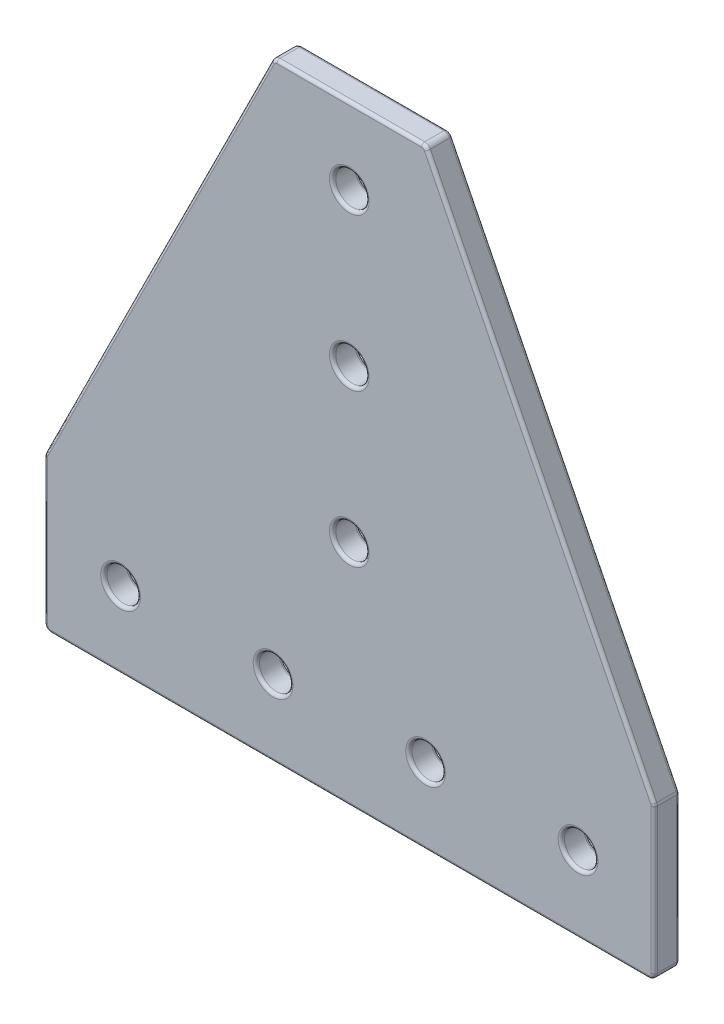
SolidWorks part; units mm, degrees
ref_plane "Front Plane" through (0, 0, 0) normal (0, 0, 1) x (1, 0, 0)
ref_plane "Top Plane" through (0, 0, 0) normal (0, 1, 0) x (1, 0, 0)
ref_plane "Right Plane" through (0, 0, 0) normal (1, 0, 0) x (0, 0, -1)
sketch "Sketch1" plane through (0, 0, 0) normal (0, 0, 1) x (1, 0, 0)
  line L1 (-76.2, -19.05) -> (76.2, -19.05) construction
  line L2 (76.2, -19.05) -> (76.2, 19.05) construction
  line L3 (76.2, 19.05) -> (19.05, 133.35) construction
  line L4 (19.05, 133.35) -> (-19.05, 133.35) construction
  line L6 (-19.05, 0) -> (-57.15, 0) construction
  line L7 (-72.0857, 8.1026) -> (-52.9331, 8.1026) construction
  line L8 (-72.0857, -8.1026) -> (-52.9331, -8.1026) construction
  line L9 (-76.2, -19.05) -> (-76.2, 19.05)
  line L10 (-76.2, 19.05) -> (-19.05, 133.35) construction
  line L11 (-19.05, 0) -> (19.05, 0) construction
  line L12 (19.05, 0) -> (57.15, 0) construction
  line L13 (0, 0) -> (0, 38.1) construction
  line L14 (0, 38.1) -> (0, 76.2) construction
  line L15 (0, 76.2) -> (0, 114.3) construction
  circle A0 centre (-57.15, 0) radius 4.1656 construction
  circle A1 centre (-19.05, 0) radius 4.1656 construction
  circle A4 centre (-57.15, 0) radius 3.9687 construction
  arc A6 (-72.0857, 8.1026) -> (-72.0857, -8.1026) centre (-62.3062, 0) ccw construction
  circle A7 centre (19.05, 0) radius 4.1656 construction
  arc A8 (-52.9331, -8.1026) -> (-52.9331, 8.1026) centre (-62.7126, 0) ccw construction
  circle A9 centre (57.15, 0) radius 4.1656 construction
  circle A10 centre (0, 38.1) radius 4.1656 construction
  circle A11 centre (0, 76.2) radius 4.1656 construction
  circle A12 centre (0, 114.3) radius 4.1656 construction
  point P4 (0, 0)
  point P9 (0, -19.05)
  point P14 (0, 133.35)
  point P20 (-75.0062, 0)
  point P21 (-50.0126, 0)
  point P25 (-57.15, -3.9688)
  point P31 (-57.15, 3.9688)
  dimension "Mounting Hole Diameter" = 8.3312
  dimension "Thread Diameter" = 7.9375
  dimension "D2" = 12.7
  dimension "Length" = 152.4
  dimension "Width" = 152.4
  dimension "Flat Length" = 38.1
  dimension "Flat Width" = 38.1
  dimension "Hole Height" = 19.05
  dimension "Nut Width" = 24.9936
  dimension "D13" = 7.1374
  dimension "Nut Height" = 16.2052
  dimension "Mounting Hole Spacing" = 38.1
sketch "Sketch2" plane through (0, 0, 0) normal (1, 0, 0) x (0, 0, -1)
  line L0 (3.175, 0) -> (8.8138, 0) construction
  line L1 (-3.175, 133.35) -> (3.175, 133.35) construction
  line L2 (-3.175, 133.35) -> (-3.175, -19.05) construction
  line L3 (-3.175, -19.05) -> (3.175, -19.05) construction
  line L4 (3.175, 133.35) -> (3.175, -19.05) construction
  line L6 (-7.3914, 0) -> (14.2748, 0)
  line L12 (-7.3914, 2.3812) -> (-7.3914, -2.3813)
  line L13 (-3.175, 8.382) -> (-3.175, -8.382)
  line L14 (14.2748, 3.9687) -> (14.2748, -3.9687)
  line L15 (14.1866, 4.1215) -> (14.8922, 2.8994)
  line L16 (14.8922, 2.8994) -> (15.5977, 4.1215)
  line L17 (15.5977, 4.1215) -> (14.1866, 4.1215)
  line L18 (14.8922, 4.1215) -> (14.8922, 3.9687)
  line L19 (14.8922, 2.8994) -> (14.8922, 3.0522)
  line L20 (14.2748, 3.9687) -> (15.5095, 3.9687)
  line L21 (14.2307, 4.0451) -> (15.5536, 4.0451)
  line L22 (14.804, 3.0522) -> (14.9804, 3.0522)
  point P4 (0, 133.35)
  point P9 (5.207, 0)
  point P10 (-4.699, 0)
  point P16 (-7.3914, 0)
  point P19 (-3.175, 0)
  point P22 (14.2748, 0)
  point P34 (14.8922, 3.9687)
  point P36 (14.8922, 4.0451)
  point P39 (14.8922, 3.0522)
  dimension "Thickness" = 6.35
  dimension "Nut Thickness" = 5.6388
  dimension "D3" = 2.032
  dimension "Screw Head Height" = 4.2164
  dimension "D5" = 1.524
  dimension "Hex Size" = 4.7625
  dimension "Mounting Fastener Thread Length" = 17.4498
  dimension "Screw Head Diameter" = 16.764
  dimension "Thread Pitch" = 1.4111
  dimension "D10" = 0.1764
sketch "Sketch3" plane through (0, 0, 0) normal (0, 0, 1) x (1, 0, 0)
  line L0 (76.2, -19.05) -> (76.2, 19.05) construction
  line L1 (-76.2, -19.05) -> (76.2, -19.05) construction
  line L3 (76.2, 19.05) -> (19.05, 133.35) construction
  line L4 (19.05, 133.35) -> (-19.05, 133.35) construction
  line L5 (76.2, -19.05) -> (76.2, 19.05)
  line L6 (-76.2, -19.05) -> (76.2, -19.05)
  line L8 (76.2, 19.05) -> (19.05, 133.35)
  line L9 (19.05, 133.35) -> (-19.05, 133.35)
  line L10 (-19.05, 133.35) -> (-76.2, 19.05)
  line L11 (-76.2, 19.05) -> (-76.2, -19.05)
  circle A0 centre (-57.15, 0) radius 4.1656 construction
  circle A1 centre (-19.05, 0) radius 4.1656 construction
  circle A2 centre (57.15, 0) radius 4.1656 construction
  circle A3 centre (19.05, 0) radius 4.1656 construction
  circle A4 centre (-57.15, 0) radius 4.1656
  circle A5 centre (-19.05, 0) radius 4.1656
  circle A6 centre (0, 38.1) radius 4.1656 construction
  circle A7 centre (0, 76.2) radius 4.1656 construction
  circle A8 centre (0, 114.3) radius 4.1656 construction
  circle A9 centre (57.15, 0) radius 4.1656
  circle A10 centre (19.05, 0) radius 4.1656
  circle A11 centre (0, 38.1) radius 4.1656
  circle A12 centre (0, 76.2) radius 4.1656
  circle A13 centre (0, 114.3) radius 4.1656
extrude "Boss-Extrude1" add sketch "Sketch3" along normal up to vertex (3.175 mm away) and the other way up to vertex (3.175 mm away) up to point (0, -19.05, 3.175) other way up to point (0, -19.05, -3.175)
fillet "Fillet1" radius 1.5875 6 edges at (76.2, -19.05, 0) (19.05, 133.35, 0) (76.2, 19.05, 0) (-76.2, -19.05, 0) (-76.2, 19.05, 0) (-19.05, 133.35, 0)
fillet "Fillet2" radius 0.7937 38 edges at (75.735, -18.585, -3.175) (76.2, 0.6064, -3.175) (76.1575, 19.04, -3.175) (47.7606, 75.9288, -3.175) (18.9035, 133.1129, -3.175) (0, 133.35, -3.175) (0, -19.05, -3.175) (-52.9844, 0, -3.175) (-14.8844, 0, -3.175) (-14.8844, 0, 3.175) (0, 133.35, 3.175) (18.9035, 133.1129, 3.175) (47.7606, 75.9288, 3.175) (76.1575, 19.04, 3.175) (76.2, 0.6064, 3.175) (75.735, -18.585, 3.175) (0, -19.05, 3.175) (-52.9844, 0, 3.175) (-18.9035, 133.1129, -3.175) (-47.7606, 75.9288, -3.175) (-76.1575, 19.04, -3.175) (-76.2, 0.6064, -3.175) (-75.735, -18.585, -3.175) (61.3156, 0, -3.175) (23.2156, 0, -3.175) (4.1656, 38.1, -3.175) (4.1656, 76.2, -3.175) (4.1656, 114.3, -3.175) (4.1656, 114.3, 3.175) (4.1656, 38.1, 3.175) (61.3156, 0, 3.175) (-76.1575, 19.04, 3.175) (-47.7606, 75.9288, 3.175) (-18.9035, 133.1129, 3.175) (-75.735, -18.585, 3.175) (-76.2, 0.6064, 3.175) (23.2156, 0, 3.175) (4.1656, 76.2, 3.175)
ref_plane "Plane1" through (-57.15, 0, 0) normal (1, 0, 0) x (0, 0, -1)
sketch "Sketch9" plane through (0, 0, 3.175) normal (0, 0, 1) x (1, 0, 0)
  point P0 (19.05, 0)
  point P1 (57.15, 0)
  point P2 (-19.05, 0)
  point P3 (0, 114.3)
  point P5 (0, 76.2)
  point P7 (0, 38.1)
sketch "Sketch11" plane through (0, 0, 0) normal (1, 0, 0) x (0, 0, -1)
  line L0 (14.2748, 3.9687) -> (15.5095, 3.9687) construction
  line L1 (14.2748, 3.9687) -> (14.2748, -3.9687) construction
  point P0 (3.175, 133.35)
  point P1 (-3.175, 133.35)
  point P3 (-3.175, -19.05)
  point P5 (14.2748, -3.9687)
  point P7 (12.8637, 3.9687)
  dimension "D1" = 1.4111
equation "\"D10@Sketch2\" = \"Thread Pitch@Sketch2\" / 8"
equation "\"D1@Fillet1\"=\"Thickness@Sketch2\"*.25"
equation "\"D1@Fillet2\"=\"D1@Fillet1\"*.5"
equation "\"D1@Sketch11\"=\"Thread Pitch@Sketch2\""
